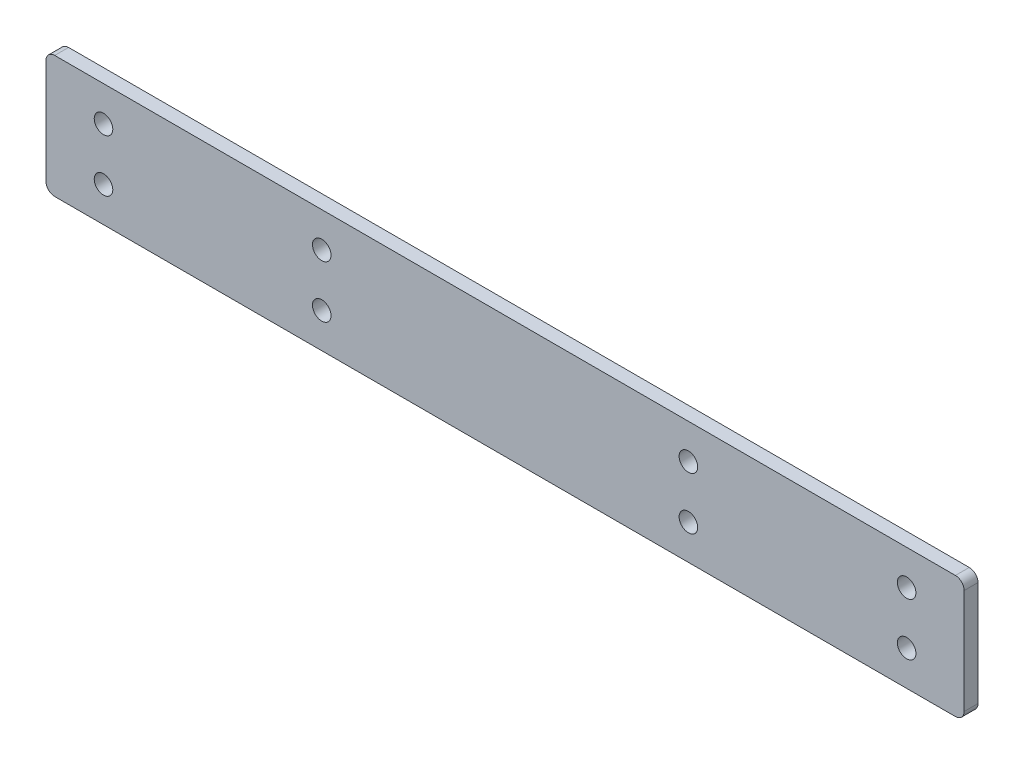
SolidWorks part; units mm, degrees
ref_plane "Front Plane" through (0, 0, 0) normal (0, 0, 1) x (1, 0, 0)
ref_plane "Top Plane" through (0, 0, 0) normal (0, 1, 0) x (1, 0, 0)
ref_plane "Right Plane" through (0, 0, 0) normal (1, 0, 0) x (0, 0, -1)
sketch "Sketch1" plane through (0, 0, 0) normal (0, 0, 1) x (1, 0, 0)
  line L0 (-105.175, 0) -> (105.175, 0) construction
  line L1 (-105.175, -14) -> (105.175, -14)
  line L2 (-105.175, -14) -> (-105.175, 14)
  line L3 (-105.175, 14) -> (105.175, 14)
  line L4 (105.175, -14) -> (105.175, 14)
  line L5 (-105.175, -14) -> (105.175, 14) construction
  line L6 (-105.175, 14) -> (105.175, -14) construction
  line L7 (0, 14) -> (0, -14) construction
  circle A0 centre (92, 6) radius 2.125
  circle A1 centre (92, -6) radius 2.125
  circle A2 centre (-92, -6) radius 2.125
  circle A3 centre (-92, 6) radius 2.125
  circle A4 centre (-42, 6) radius 2.125
  circle A5 centre (-42, -6) radius 2.125
  circle A6 centre (42, -6) radius 2.125
  circle A7 centre (42, 6) radius 2.125
  point P0 (0, 0)
  dimension "D2" = 4.25
  dimension "D5" = 4.25
  dimension "D1" = 210.35
  dimension "D3" = 6
  dimension "D4" = 8
  dimension "D6" = 50
  dimension "D7" = 13.175
extrude "Boss-Extrude1" add sketch "Sketch1" along normal blind 3.175
fillet "Fillet1" radius 2 4 edges at (105.175, -14, 1.5875) (105.175, 14, 1.5875) (-105.175, -14, 1.5875) (-105.175, 14, 1.5875)
